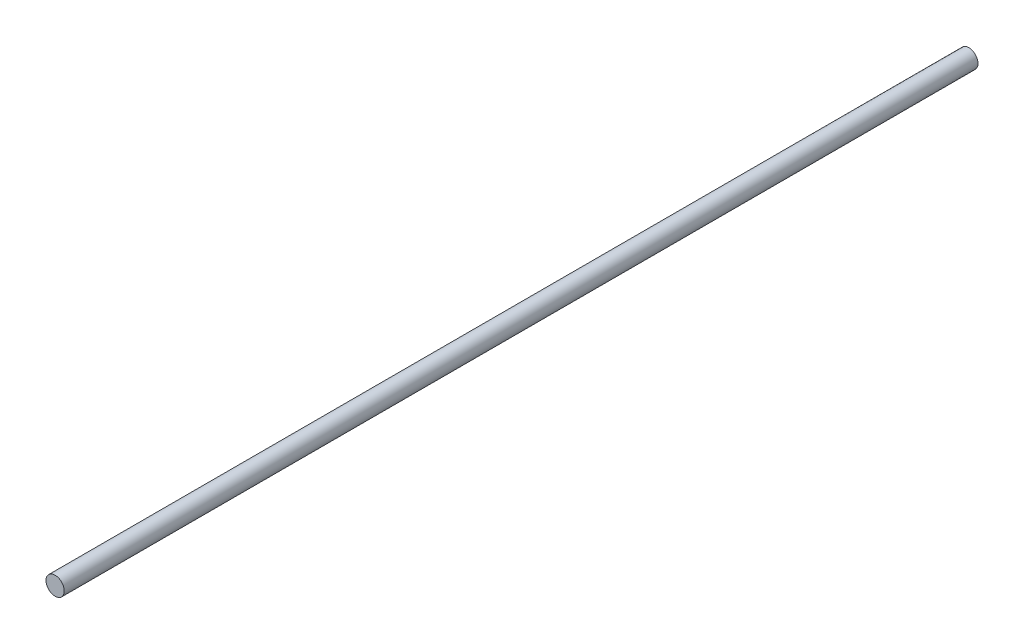
SolidWorks part; units mm, degrees
ref_plane "Alzado" through (0, 0, 0) normal (0, 0, 1) x (1, 0, 0)
ref_plane "Planta" through (0, 0, 0) normal (0, 1, 0) x (1, 0, 0)
ref_plane "Vista lateral" through (0, 0, 0) normal (1, 0, 0) x (0, 0, -1)
sketch "Croquis1" plane through (0, 0, 0) normal (0, 0, 1) x (1, 0, 0)
  circle A0 centre (0, 0) radius 4
  dimension "D1" = 8
extrude "Saliente-Extruir1" add sketch "Croquis1" along normal blind 400
